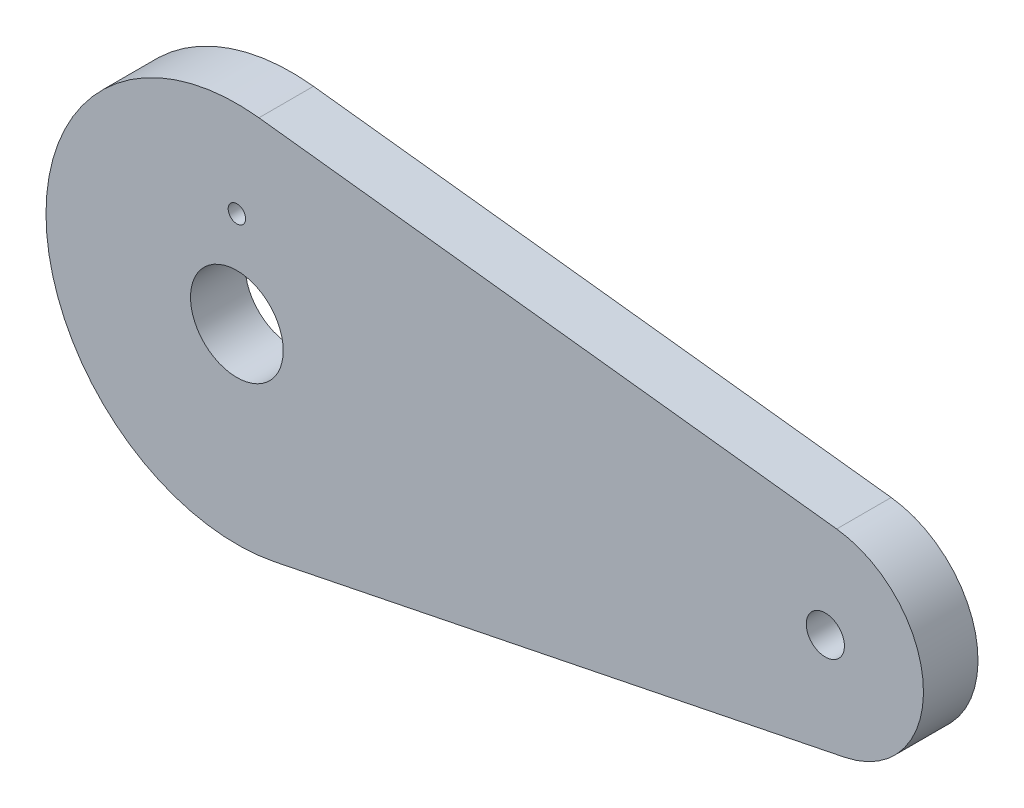
SolidWorks part; units mm, degrees
ref_plane "Front Plane" through (0, 0, 0) normal (0, 0, 1) x (1, 0, 0)
ref_plane "Top Plane" through (0, 0, 0) normal (0, 1, 0) x (1, 0, 0)
ref_plane "Right Plane" through (0, 0, 0) normal (1, 0, 0) x (0, 0, -1)
sketch "Sketch1" plane through (0, 0, 0) normal (0, 0, 1) x (1, 0, 0)
  line L0 (-20.22, 57.58) -> (33.7318, 59.8603) construction
  line L1 (-20.22, 57.58) -> (33.7318, 59.8603) construction
  line L2 (-18.1976, 74.9627) -> (34.7719, 68.8)
  line L3 (-16.7381, 40.4299) -> (35.5225, 51.0402)
  line L4 (-20.22, 57.58) -> (-20.22, 66.33) construction
  circle A0 centre (-20.22, 57.58) radius 17.5 construction
  circle A1 centre (-20.22, 57.58) radius 17.5 construction
  circle A2 centre (33.7318, 59.8603) radius 9 construction
  circle A3 centre (-20.22, 57.58) radius 4.25
  circle A4 centre (33.7318, 59.8603) radius 1.75
  arc A5 (-18.1976, 74.9627) -> (-16.7381, 40.4299) centre (-20.22, 57.58) ccw
  arc A6 (34.7719, 68.8) -> (35.5225, 51.0402) centre (33.7318, 59.8603) cw
  circle A7 centre (-20.22, 66.33) radius 0.8
  dimension "D1" = 18
  dimension "D2" = 3.5
  dimension "D3" = 8.5
  dimension "D5" = 1.6
  dimension "D4" = 8.75
extrude "Boss-Extrude1" add sketch "Sketch1" against normal blind 5
